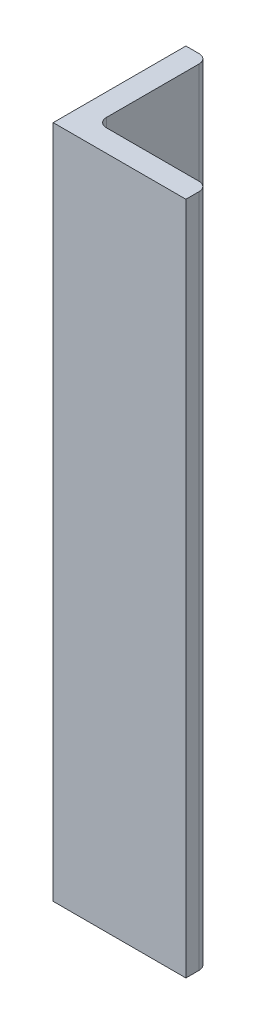
SolidWorks part; units mm, degrees
material "6061-T6 (SS)"
ref_plane "Front Plane" through (0, 0, 0) normal (0, 0, 1) x (1, 0, 0)
ref_plane "Top Plane" through (0, 0, 0) normal (0, 1, 0) x (1, 0, 0)
ref_plane "Right Plane" through (0, 0, 0) normal (1, 0, 0) x (0, 0, -1)
sketch "Sketch1" plane through (0, 0, 0) normal (0, 1, 0) x (1, 0, 0)
  line L0 (0, 0) -> (0, 19.05)
  line L1 (0, 19.05) -> (1.905, 19.05)
  line L2 (3.175, 17.78) -> (3.175, 4.445)
  line L3 (4.445, 3.175) -> (17.78, 3.175)
  line L4 (19.05, 1.905) -> (19.05, 0)
  line L5 (19.05, 0) -> (0, 0)
  arc A0 (1.905, 19.05) -> (3.175, 17.78) centre (1.905, 17.78) cw
  arc A1 (17.78, 3.175) -> (19.05, 1.905) centre (17.78, 1.905) cw
  arc A2 (3.175, 4.445) -> (4.445, 3.175) centre (4.445, 4.445) ccw
  point P9 (3.175, 19.05)
  dimension "D2" = 1.27
  dimension "D4" = 1.27
  dimension "D1" = 19.05
  dimension "D3" = 3.175
extrude "Boss-Extrude1" add sketch "Sketch1" along normal blind 96.8248
